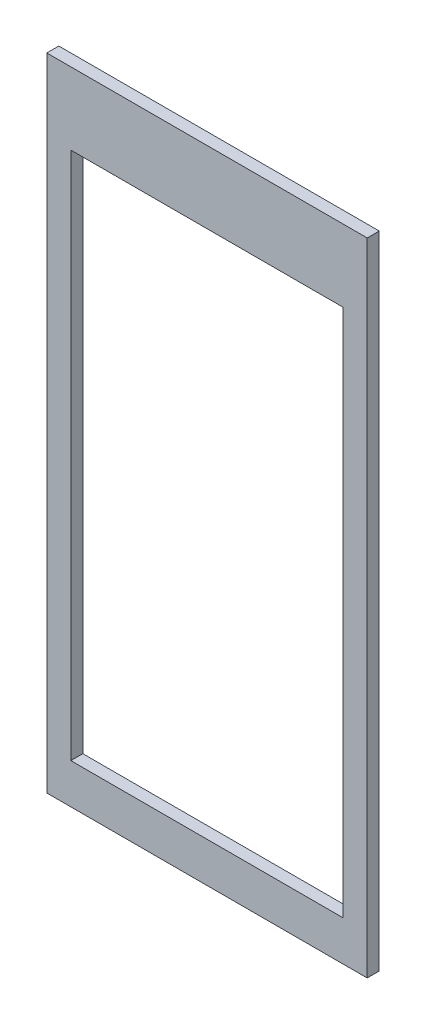
SolidWorks part; units mm, degrees
ref_plane "Front Plane" through (0, 0, 0) normal (0, 0, 1) x (1, 0, 0)
ref_plane "Top Plane" through (0, 0, 0) normal (0, 1, 0) x (1, 0, 0)
ref_plane "Right Plane" through (0, 0, 0) normal (1, 0, 0) x (0, 0, -1)
sketch "Sketch1" plane through (0, 0, 0) normal (0, 0, 1) x (1, 0, 0)
  line L1 (0, 0) -> (40, 0)
  line L2 (0, 0) -> (0, 80)
  line L3 (0, 80) -> (40, 80)
  line L4 (40, 0) -> (40, 80)
  dimension "D1" = 40
  dimension "D2" = 80
extrude "Boss-Extrude1" add sketch "Sketch1" along normal blind 1.5 contours L2 L3 L4 L1
sketch "Sketch2" plane through (0, 0, 1.5) normal (0, 0, 1) x (1, 0, 0)
  line L0 (0, 40) -> (3, 40)
  line L1 (0, 0) -> (0, 80) construction
  line L2 (40, 0) -> (40, 80) construction
  line L3 (20, 40) -> (20, 71) construction
  line L4 (20, 40) -> (20, 5) construction
  line L5 (20, 5) -> (20, 0)
  line L6 (0, 0) -> (40, 0) construction
  line L7 (3, 71) -> (0, 71)
  line L8 (3, 71) -> (3, 5)
  line L9 (20, 5) -> (3, 5)
  line L10 (20, 5) -> (37, 5)
  line L11 (3, 71) -> (37, 71)
  line L12 (37, 71) -> (40, 71)
  line L13 (37, 71) -> (37, 5)
  line L14 (3, 40) -> (20, 40) construction
  line L15 (37, 40) -> (40, 40)
  line L16 (20, 40) -> (37, 40) construction
  dimension "D1" = 35
  dimension "D2" = 31
  dimension "D3" = 5
  dimension "D4" = 3
  dimension "D5" = 3
  dimension "D6" = 34
extrude "Cut-Extrude1" cut sketch "Sketch2" against normal up to surface (1.5 mm away) contours L13 L11 L8 L9 L10 up to face at (20, 40, 0)
